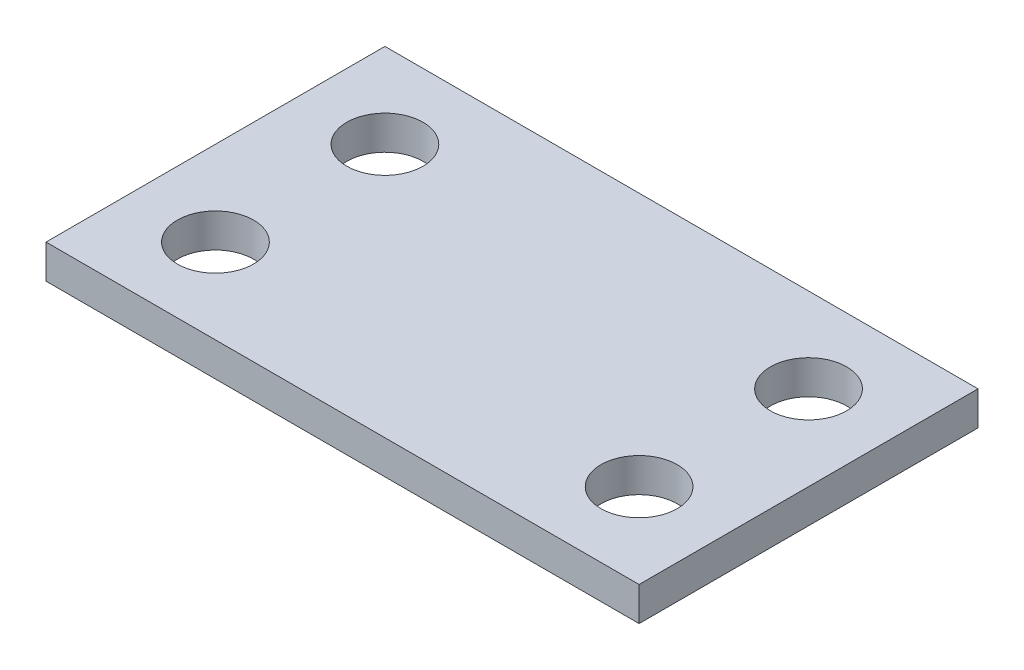
SolidWorks part; units mm, degrees
ref_plane "Płaszczyzna przednia" through (0, 0, 0) normal (0, 0, 1) x (1, 0, 0)
ref_plane "Płaszczyzna górna" through (0, 0, 0) normal (0, 1, 0) x (1, 0, 0)
ref_plane "Płaszczyzna prawa" through (0, 0, 0) normal (1, 0, 0) x (0, 0, -1)
sketch "Szkic1" plane through (0, 0, 0) normal (0, 1, 0) x (1, 0, 0)
  line L1 (0, 0) -> (140, 0)
  line L2 (0, 0) -> (0, 80)
  line L3 (0, 80) -> (140, 80)
  line L4 (140, 0) -> (140, 80)
  circle A0 centre (20, 60) radius 9
  circle A1 centre (120, 60) radius 9
  circle A2 centre (120, 20) radius 9
  circle A3 centre (20, 20) radius 9
  dimension "D3" = 18
  dimension "D4" = 20
  dimension "D5" = 20
  dimension "D1" = 140
  dimension "D2" = 80
  dimension "D6" = 2
  dimension "D7" = 2
extrude "Dodanie-wyciągnięcie1" add sketch "Szkic1" along normal blind 8
